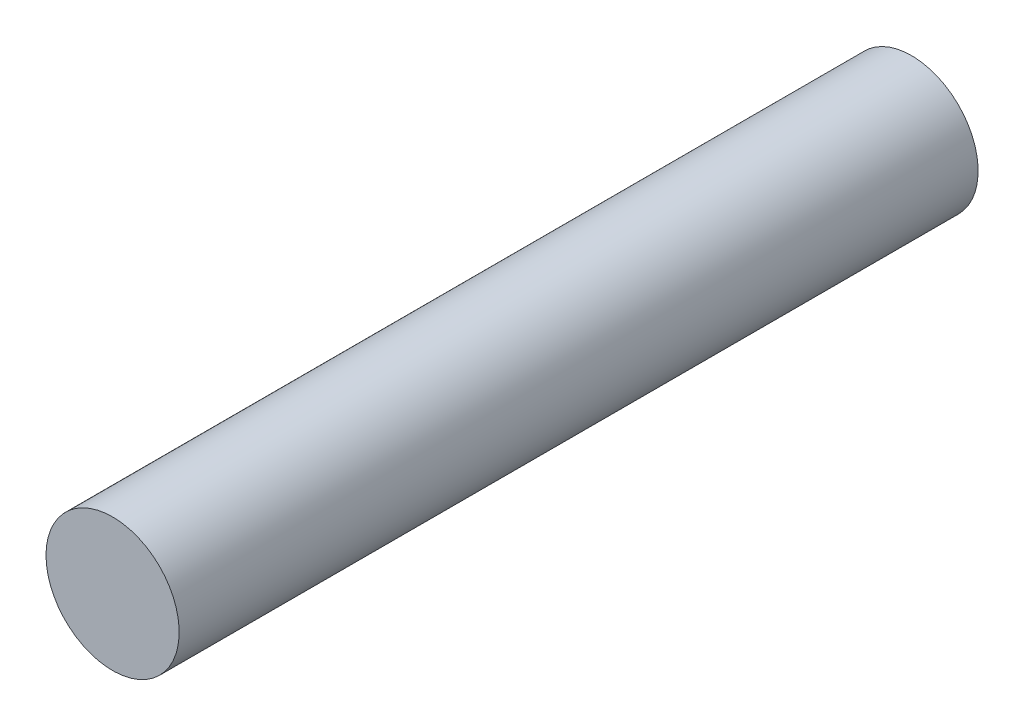
SolidWorks part; units mm, degrees
ref_plane "Plan de face" through (0, 0, 0) normal (0, 0, 1) x (1, 0, 0)
ref_plane "Plan de dessus" through (0, 0, 0) normal (0, 1, 0) x (1, 0, 0)
ref_plane "Plan de droite" through (0, 0, 0) normal (1, 0, 0) x (0, 0, -1)
sketch "Esquisse1" plane through (0, 0, 0) normal (0, 0, 1) x (1, 0, 0)
  circle A0 centre (0, 0) radius 6.35
  dimension "D1" = 12.7
extrude "Boss.-Extru.1" add sketch "Esquisse1" along normal blind 76.2
